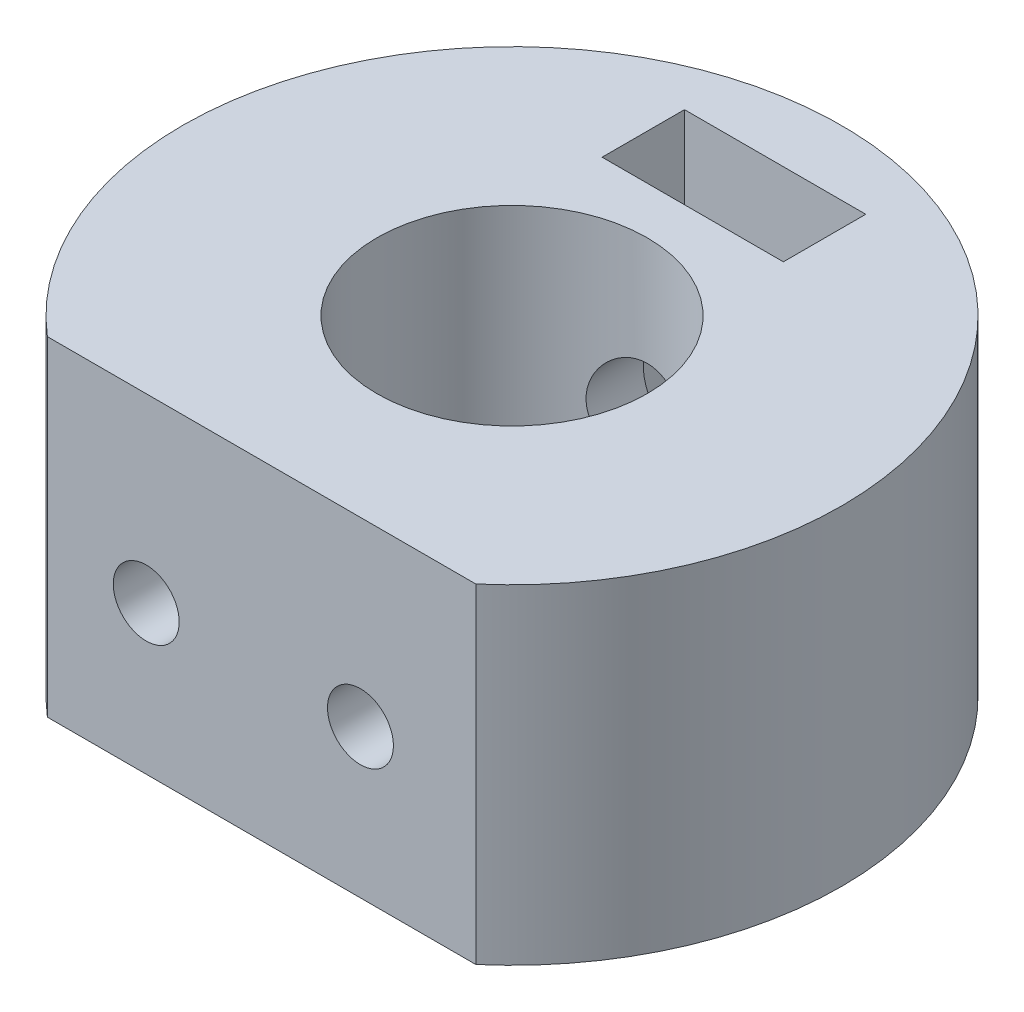
SolidWorks part; units mm, degrees
ref_plane "前视基准面" through (0, 0, 0) normal (0, 0, 1) x (1, 0, 0)
ref_plane "上视基准面" through (0, 0, 0) normal (0, 1, 0) x (1, 0, 0)
ref_plane "右视基准面" through (0, 0, 0) normal (1, 0, 0) x (0, 0, -1)
sketch "草图1" plane through (0, 0, 0) normal (0, 1, 0) x (1, 0, 0)
  circle A0 centre (0, 0) radius 10
  circle A1 centre (0, 0) radius 4.1
  dimension "D1" = 20
  dimension "D2" = 8.2
extrude "凸台-拉伸1" add sketch "草图1" along normal blind 10
sketch "草图2" plane through (0, 10, 0) normal (0, 1, 0) x (1, 0, 0)
  line L0 (-6.5, -7.5993) -> (6.5, -7.5993)
  circle A0 centre (0, 0) radius 10 construction
  arc A1 (-6.5, -7.5993) -> (6.5, -7.5993) centre (0, 0) ccw
  dimension "D1" = 13
extrude "切除-拉伸1" cut sketch "草图2" against normal through all
sketch "草图3" plane through (0, 0, 7.5993) normal (0, 0, 1) x (1, 0, 0)
  line L0 (6.5, 0) -> (-6.5, 0) construction
  line L1 (6.5, 0) -> (6.5, 10) construction
  circle A0 centre (-3.5, 4.5) radius 1
  circle A1 centre (3, 4.5) radius 1
  dimension "D2" = 2
  dimension "D3" = 2
  dimension "D4" = 4.5
  dimension "D5" = 3.5
  dimension "D1" = 6.5
extrude "切除-拉伸2" cut sketch "草图3" against normal blind 7
ref_plane "基准面1" through (0, 0, -2.4007) normal (0, 0, 1) x (1, 0, 0)
sketch "草图4" plane through (0, 0, -2.4007) normal (0, 0, 1) x (1, 0, 0)
  circle A0 centre (0, 5.1488) radius 1.55
  dimension "D1" = 3.1
extrude "切除-拉伸3" cut sketch "草图4" against normal blind 11
sketch "草图5" plane through (0, 10, 0) normal (0, 1, 0) x (1, 0, 0)
  line L1 (-2.7991, 8.0328) -> (2.7009, 8.0328)
  line L2 (-2.7991, 8.0328) -> (-2.7991, 5.5328)
  line L3 (-2.7991, 5.5328) -> (2.7009, 5.5328)
  line L4 (2.7009, 8.0328) -> (2.7009, 5.5328)
  dimension "D1" = 2.5
  dimension "D2" = 5.5
extrude "切除-拉伸4" cut sketch "草图5" against normal blind 8
